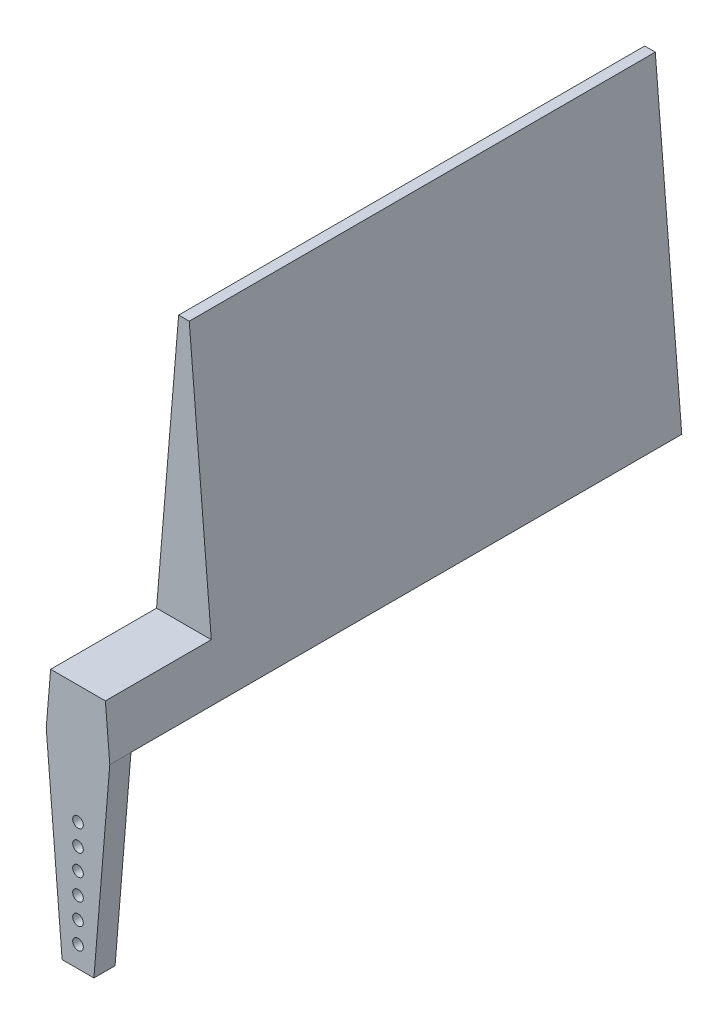
SolidWorks part; units mm, degrees
ref_plane "Front Plane" through (0, 0, 0) normal (0, 0, 1) x (1, 0, 0)
ref_plane "Top Plane" through (0, 0, 0) normal (0, 1, 0) x (1, 0, 0)
ref_plane "Right Plane" through (0, 0, 0) normal (1, 0, 0) x (0, 0, -1)
sketch "Sketch1" plane through (0, 0, 0) normal (0, 0, 1) x (1, 0, 0)
  line L0 (53, 50.7279) -> (74.1445, 50.7279) construction
  line L1 (63.0722, 50.7279) -> (64.0722, 50.7279)
  line L2 (64.0722, 50.7279) -> (66.5722, 20.7279)
  line L3 (63.5722, 20.7279) -> (63.5722, 50.7279) construction
  line L4 (63.0722, 50.7279) -> (60.5722, 20.7279)
  line L11 (54, 20.7279) -> (60.5722, 20.7279) construction
  line L16 (66.5722, 20.7279) -> (73.1445, 20.7279) construction
  line L17 (60.5722, 20.7279) -> (66.5722, 20.7279)
  point P1 (63.5722, 20.7279)
  point P19 (63.5722, 50.7279)
  point P20 (63.5722, 50.7279)
  dimension "D2" = 1
  dimension "D1" = 6
  dimension "D3" = 30
extrude "Boss-Extrude1" add sketch "Sketch1" against normal blind 44
sketch "Sketch3" plane through (0, 0, 0) normal (0, 0, 1) x (1, 0, 0)
  line L0 (60.5722, 20.7279) -> (60.9889, 25.7279)
  line L1 (63.0722, 50.7279) -> (60.5722, 20.7279) construction
  line L2 (60.9889, 25.7279) -> (66.1556, 25.7279)
  line L3 (66.5722, 20.7279) -> (64.0722, 50.7279) construction
  line L4 (66.1556, 25.7279) -> (66.5722, 20.7279)
  line L5 (66.5722, 20.7279) -> (60.5722, 20.7279)
  dimension "D1" = 5
extrude "Boss-Extrude3" add sketch "Sketch3" along normal blind 10
sketch "Sketch4" plane through (0, 0, 10) normal (0, 0, 1) x (1, 0, 0)
  line L1 (63.5722, 4.5279) -> (63.5722, 2.5279) construction
  line L5 (66.5722, 20.7279) -> (60.5722, 20.7279)
  line L7 (63.5722, 14.5279) -> (63.5722, 20.7279) construction
  line L12 (63.5722, 12.5279) -> (63.5722, 14.5279) construction
  line L13 (63.5722, 10.5279) -> (63.5722, 12.5279) construction
  line L14 (63.5722, 8.5279) -> (63.5722, 10.5279) construction
  line L15 (63.5722, 6.5279) -> (63.5722, 8.5279) construction
  line L16 (63.5722, 4.5279) -> (63.5722, 6.5279) construction
  line L17 (65.0722, 2.5279) -> (66.5722, 20.7279)
  line L18 (62.0722, 2.5279) -> (65.0722, 2.5279)
  line L19 (60.5722, 20.7279) -> (62.0722, 2.5279)
  circle A20 centre (63.5722, 14.5279) radius 0.5
  circle A24 centre (63.5722, 12.5279) radius 0.5
  circle A26 centre (63.5722, 10.5279) radius 0.5
  circle A28 centre (63.5722, 8.5279) radius 0.5
  circle A30 centre (63.5722, 4.5279) radius 0.5
  circle A32 centre (63.5722, 6.5279) radius 0.5
  point P13 (63.5722, 20.7279)
  dimension "D2" = 6.2
  dimension "D3" = 2
  dimension "D1" = 1
  dimension "D4" = 3
extrude "Boss-Extrude4" add sketch "Sketch4" against normal blind 2
equation "\"FlipperDepth\"=44"
equation "\"D1@Boss-Extrude1\"=\"FlipperDepth\""
equation "\"FlipperHandleLength\"=10"
equation "\"D1@Boss-Extrude3\"=\"FlipperHandleLength\""
equation "\"FlipperConnectionToServoHeight\"=18"
equation "\"FlipperHeight\"=30"
equation "\"D3@Sketch1\"=\"FlipperHeight\""
